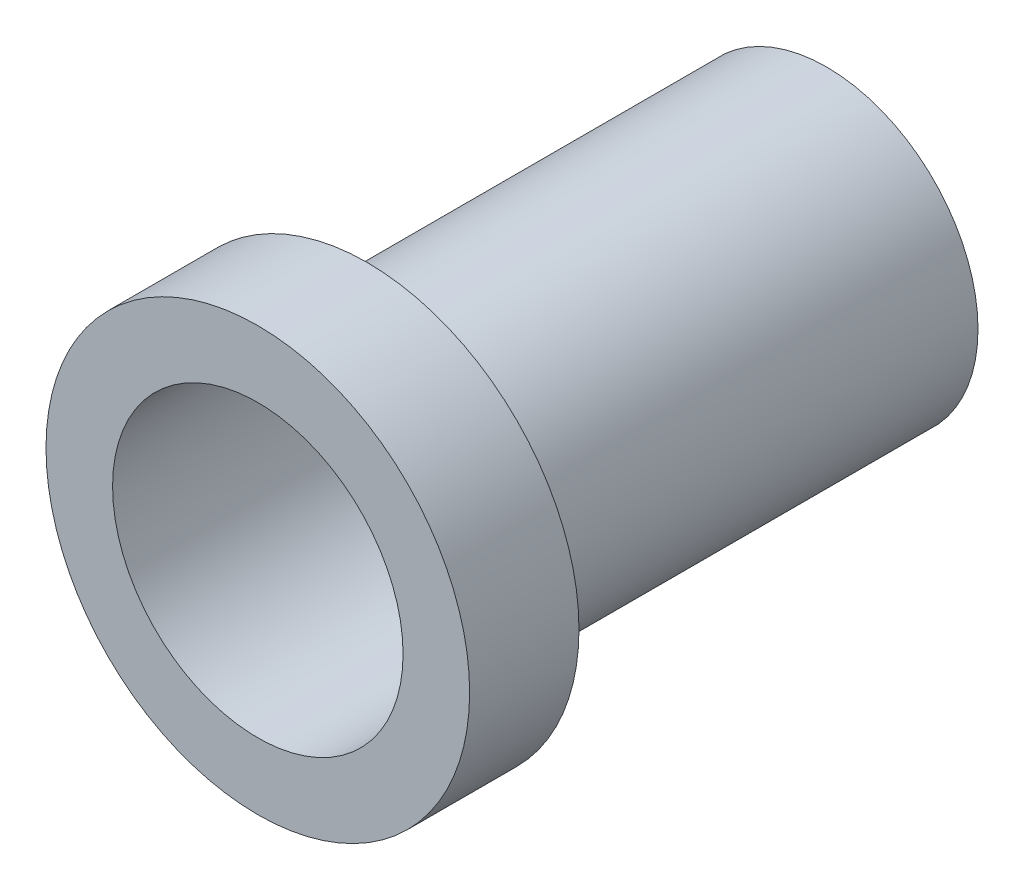
SolidWorks part; units mm, degrees
ref_plane "Спереди" through (0, 0, 0) normal (0, 0, 1) x (1, 0, 0)
ref_plane "Сверху" through (0, 0, 0) normal (0, 1, 0) x (1, 0, 0)
ref_plane "Справа" through (0, 0, 0) normal (1, 0, 0) x (0, 0, -1)
sketch "Эскиз1" plane through (0, 0, 0) normal (0, 0, 1) x (1, 0, 0)
  circle A0 centre (0, 0) radius 12
  circle A1 centre (0, 0) radius 12.5
  dimension "D1" = 24
  dimension "D2" = 25
extrude "Бобышка-Вытянуть1" add sketch "Эскиз1" along normal blind 40
sketch "Эскиз2" plane through (0, 0, 40) normal (0, 0, 1) x (1, 0, 0)
  circle A0 centre (0, 0) radius 17.5
  circle A2 centre (0, 0) radius 12
extrude "Бобышка-Вытянуть2" add sketch "Эскиз2" along normal blind 7 and the other way blind 1.0342
sketch "Эскиз3" plane through (0, 0, 38.9658) normal (0, 0, -1) x (-1, 0, 0)
  circle A1 centre (0, 0) radius 17.5
  circle A2 centre (0, 0) radius 17.5
  dimension "D1" = 0
extrude "Бобышка-Вытянуть3" add sketch "Эскиз3" along normal blind 1
sketch "Эскиз4" plane through (0, 0, 37.9658) normal (0, 0, -1) x (-1, 0, 0)
  circle A0 centre (0, 0) radius 12
extrude "Вырез-Вытянуть1" cut sketch "Эскиз4" against normal blind 1
